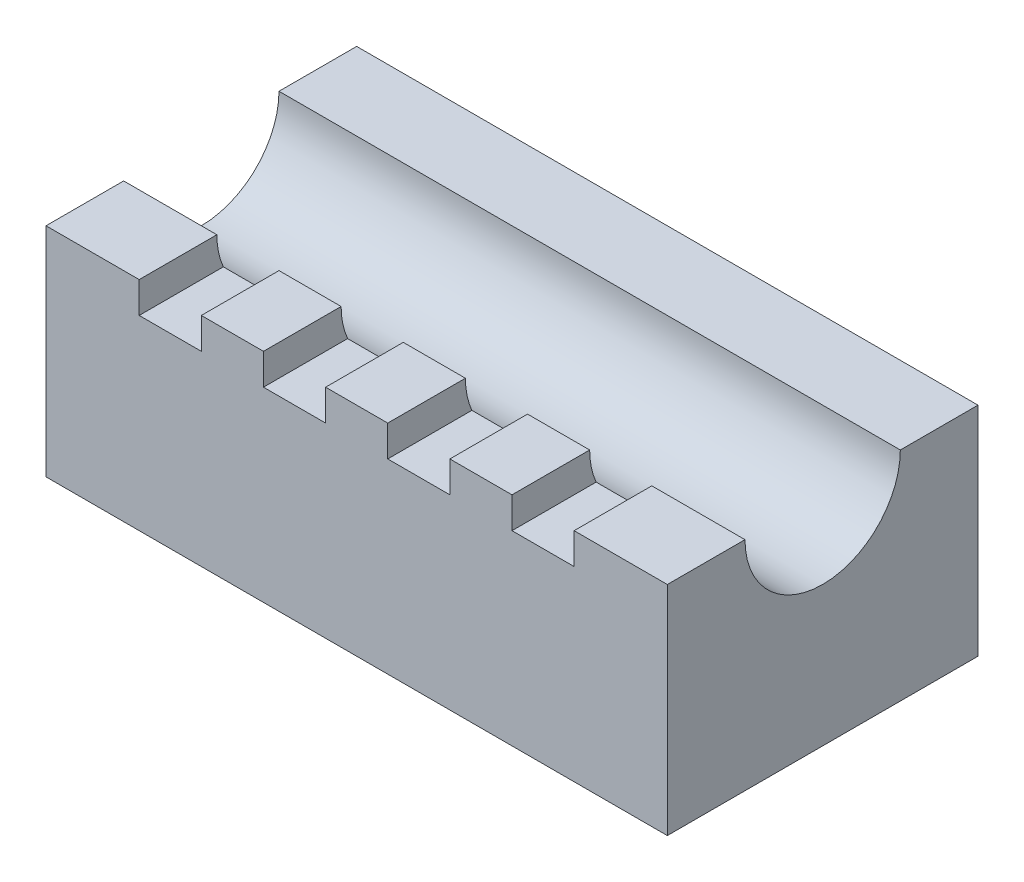
SolidWorks part; units mm, degrees
ref_plane "Front Plane" through (0, 0, 0) normal (0, 0, 1) x (1, 0, 0)
ref_plane "Top Plane" through (0, 0, 0) normal (0, 1, 0) x (1, 0, 0)
ref_plane "Right Plane" through (0, 0, 0) normal (1, 0, 0) x (0, 0, -1)
sketch "Sketch1" plane through (0, 0, 0) normal (0, 1, 0) x (1, 0, 0)
  line L1 (0, 0) -> (100, 0)
  line L2 (0, 0) -> (0, 50)
  line L3 (0, 50) -> (100, 50)
  line L4 (100, 0) -> (100, 50)
  dimension "D1" = 50
  dimension "D2" = 100
extrude "Boss-Extrude1" add sketch "Sketch1" along normal blind 35
sketch "Sketch2" plane through (100, 0, 0) normal (1, 0, 0) x (0, 0, -1)
  line L0 (0, 35) -> (50, 35) construction
  circle A1 centre (25, 35) radius 12.5
extrude "Cut-Extrude1" cut sketch "Sketch2" against normal blind 100
sketch "Sketch5" plane through (0, 0, 0) normal (0, 0, 1) x (1, 0, 0)
  line L1 (0, 35) -> (100, 35) construction
  line L10 (35, 35) -> (45, 35)
  line L11 (35, 35) -> (35, 30)
  line L12 (35, 30) -> (45, 30)
  line L13 (45, 35) -> (45, 30)
  line L31 (0, 35) -> (0, 0) construction
  line L32 (15, 35) -> (25, 35)
  line L33 (15, 35) -> (15, 30)
  line L34 (15, 30) -> (25, 30)
  line L35 (25, 35) -> (25, 30)
  line L36 (100, 35) -> (100, 0) construction
  line L37 (75, 35) -> (85, 35)
  line L38 (75, 35) -> (75, 30)
  line L39 (75, 30) -> (85, 30)
  line L40 (85, 35) -> (85, 30)
  line L42 (55, 35) -> (65, 35)
  line L43 (55, 35) -> (55, 30)
  line L44 (55, 30) -> (65, 30)
  line L45 (65, 35) -> (65, 30)
  point P16 (85, 32.5)
  line M19 (100, 35) -> (0, 35)
  dimension "D1" = 15
  dimension "D2" = 10
  dimension "D3" = 15
  dimension "D4" = 10
  dimension "D5" = 5
  dimension "D6" = 10
  dimension "D7" = 10
  dimension "D8" = 10
  dimension "D9" = 10
extrude "Cut-Extrude3" cut sketch "Sketch5" against normal blind 25 contours L35 L33 L34 M19 | L13 L11 L12 M19 | L45 L43 L44 M19 | L40 L38 L39 M19
